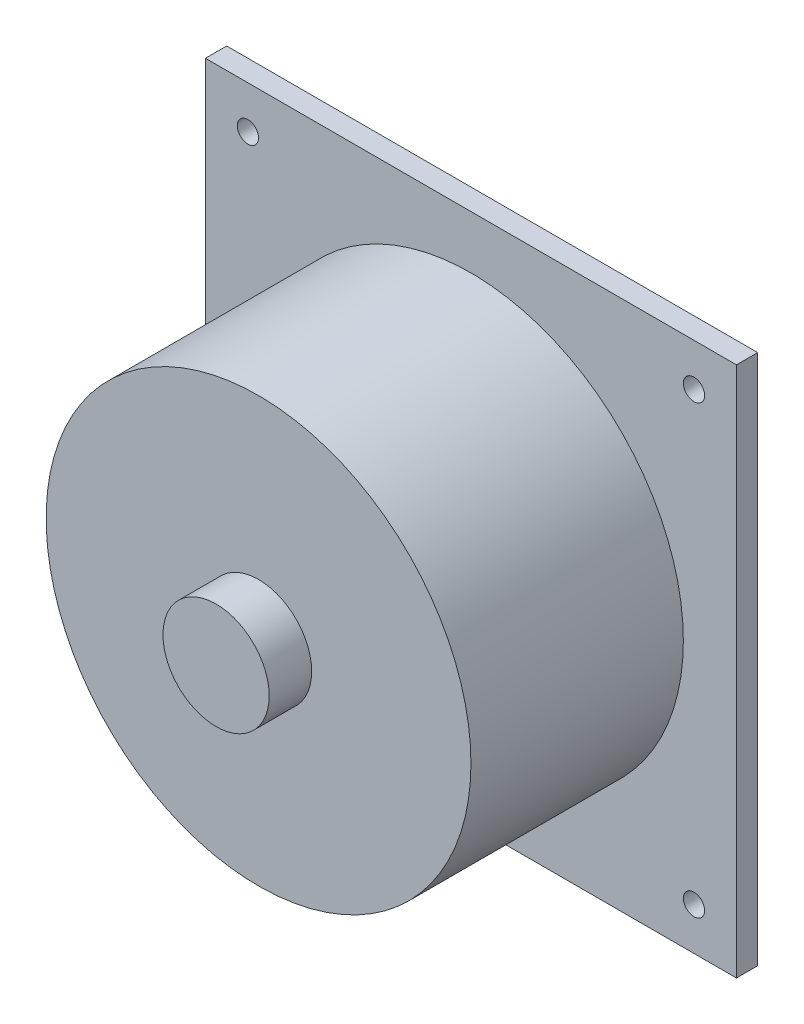
SolidWorks part; units mm, degrees
material "Plain Carbon Steel"
ref_plane "Front Plane" through (0, 0, 0) normal (0, 0, 1) x (1, 0, 0)
ref_plane "Top Plane" through (0, 0, 0) normal (0, 1, 0) x (1, 0, 0)
ref_plane "Right Plane" through (0, 0, 0) normal (1, 0, 0) x (0, 0, -1)
sketch "Sketch2" plane through (0, 0, 0) normal (0, 0, 1) x (1, 0, 0)
  line L1 (-625, 625) -> (625, 625)
  line L2 (-625, 625) -> (-625, -625)
  line L3 (-625, -625) -> (625, -625)
  line L4 (625, 625) -> (625, -625)
  point P5 (-625, 0)
  point P8 (0, 625)
  dimension "D1" = 1250
  dimension "D2" = 1250
extrude "Boss-Extrude1" add sketch "Sketch2" along normal blind 50
sketch "Sketch3" plane through (0, 0, 50) normal (0, 0, 1) x (1, 0, 0)
  circle A0 centre (0, 0) radius 500
  dimension "D1" = 1000
extrude "Boss-Extrude2" add sketch "Sketch3" along normal blind 500
sketch "Sketch4" plane through (0, 0, 50) normal (0, 0, 1) x (1, 0, 0)
  line L0 (625, 625) -> (-625, 625) construction
  line L1 (-625, 625) -> (-625, -625) construction
  line L3 (-625, -625) -> (625, -625) construction
  line L4 (625, -625) -> (625, 625) construction
  circle A0 centre (-525, 525) radius 25
  circle A1 centre (-525, -525) radius 25
  circle A2 centre (525, -525) radius 25
  circle A3 centre (525, 525) radius 25
  dimension "D1" = 50
  dimension "D2" = 100
  dimension "D3" = 100
  dimension "D4" = 100
  dimension "D5" = 100
extrude "Cut-Extrude1" cut sketch "Sketch4" against normal through all
sketch "Sketch5" plane through (0, 0, 550) normal (0, 0, 1) x (1, 0, 0)
  circle A0 centre (0, 0) radius 125
  dimension "D1" = 250
extrude "Boss-Extrude3" add sketch "Sketch5" along normal blind 100
